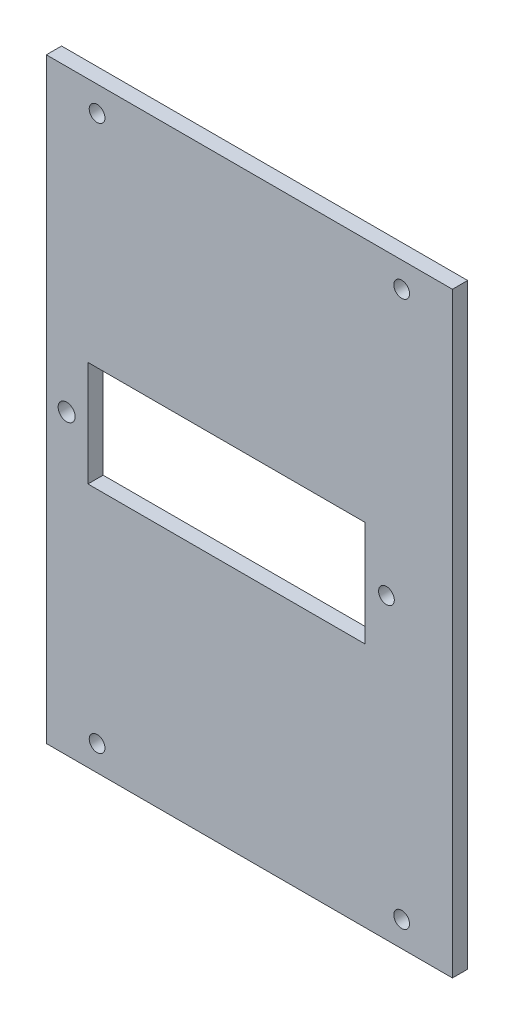
SolidWorks part; units mm, degrees
ref_plane "前视基准面" through (0, 0, 0) normal (0, 0, 1) x (1, 0, 0)
ref_plane "上视基准面" through (0, 0, 0) normal (0, 1, 0) x (1, 0, 0)
ref_plane "右视基准面" through (0, 0, 0) normal (1, 0, 0) x (0, 0, -1)
other "Configuration Table"
sketch "草图1" plane through (0, 0, 0) normal (0, 0, 1) x (1, 0, 0)
  line L0 (40, 117.5) -> (40, 94.3823) construction
  line L1 (0, 0) -> (80, 0)
  line L2 (0, 0) -> (0, 117.5)
  line L3 (0, 117.5) -> (80, 117.5)
  line L4 (80, 0) -> (80, 117.5)
  line L5 (80, 58.75) -> (41.8551, 58.75) construction
  line L7 (22.5, 66.25) -> (57.5, 66.25)
  line L8 (22.5, 66.25) -> (22.5, 51.25)
  line L9 (22.5, 51.25) -> (57.5, 51.25)
  line L10 (57.5, 66.25) -> (57.5, 51.25)
  line L11 (22.5, 66.25) -> (57.5, 51.25) construction
  line L12 (22.5, 51.25) -> (57.5, 66.25) construction
  point P9 (40, 58.75)
  point P10 (40, 58.75)
  dimension "D1" = 117.5
  dimension "D2" = 80
  dimension "D3" = 15
  dimension "D4" = 35
extrude "凸台-拉伸1" add sketch "草图1" along normal blind 3
sketch "草图2" plane through (0, 0, 3) normal (0, 0, 1) x (1, 0, 0)
  line L0 (0, 58.75) -> (80, 58.75) construction
  line L1 (0, 117.5) -> (0, 0) construction
  line L2 (80, 0) -> (80, 117.5) construction
  line L3 (40, 58.75) -> (40, 66.25) construction
  line L4 (57.5, 66.25) -> (22.5, 66.25) construction
  circle A0 centre (40, 76.75) radius 1.55
  circle A1 centre (40, 40.75) radius 1.55
  dimension "D1" = 3.1
  dimension "D2" = 18
extrude "切除-拉伸1" [suppressed] cut sketch "草图2" against normal up to next
sketch "草图3" plane through (0, 0, 3) normal (0, 0, 1) x (1, 0, 0)
  line L0 (40, 117.5) -> (40, 140.159)
  line L1 (80, 117.5) -> (0, 117.5) construction
  line L2 (22.5, 58.75) -> (37.5505, 58.75) construction
  line L3 (22.5, 66.25) -> (22.5, 51.25) construction
  circle A0 centre (10, 112.5) radius 1.55
  circle A1 centre (70, 112.5) radius 1.55
  circle A2 centre (70, 5) radius 1.55
  circle A3 centre (10, 5) radius 1.55
  dimension "D2" = 3.1
  dimension "D1" = 30
  dimension "D3" = 5
extrude "切除-拉伸2" cut sketch "草图3" against normal up to next contours A0 | A1 | A2 | A3
sketch "草图4" plane through (0, 0, 0) normal (0, 0, -1) x (-1, 0, 0)
  line L1 (-57.5, 51.25) -> (-57.5, 66.25) construction
  line L2 (0, 0) -> (-80, 0) construction
  line L3 (-40, 66.25) -> (-40, 51.25) construction
  line L4 (-57.5, 66.25) -> (-22.5, 66.25) construction
  line L5 (-22.5, 51.25) -> (-57.5, 51.25) construction
  line L6 (-57.5, 58.75) -> (-40, 58.75) construction
  circle A0 centre (-67, 58.75) radius 1.55
  circle A2 centre (-13, 58.75) radius 1.55
  dimension "D1" = 3.1
  dimension "D2" = 9.5
  dimension "D3" = 58.75
extrude "切除-拉伸3" cut sketch "草图4" against normal up to next
sketch "草图5" plane through (0, 0, 0) normal (0, 0, -1) x (-1, 0, 0)
  circle A0 centre (-4, 58.5763) radius 1.6734
extrude "切除-拉伸4" cut sketch "草图5" against normal blind 10
sketch "草图6" plane through (0, 0, 3) normal (0, 0, 1) x (1, 0, 0)
  line L0 (22.5, 66.25) -> (57.5, 51.25) construction
  line L2 (17.1936, 69.1216) -> (62.8064, 69.1216)
  line L3 (17.1936, 69.1216) -> (17.1936, 48.3784)
  line L4 (17.1936, 48.3784) -> (62.8064, 48.3784)
  line L5 (62.8064, 69.1216) -> (62.8064, 48.3784)
  line L6 (17.1936, 69.1216) -> (62.8064, 48.3784) construction
  line L7 (17.1936, 48.3784) -> (62.8064, 69.1216) construction
  point P4 (40, 58.75)
extrude "切除-拉伸5" cut sketch "草图6" against normal blind 10
sketch "草图7" plane through (17.1936, 0, 0) normal (1, 0, 0) x (0, 0, -1)
  line L4 (0, 48.3784) -> (0, 69.1216)
  line L5 (0, 69.1216) -> (-3, 69.1216)
  line L6 (-3, 69.1216) -> (-3, 48.3784)
  line L7 (-3, 48.3784) -> (0, 48.3784)
  line L8 (0, 48.3784) -> (0, 69.1216)
  line L9 (0, 69.1216) -> (-3, 69.1216)
  line L10 (-3, 69.1216) -> (-3, 48.3784)
  line L11 (-3, 48.3784) -> (0, 48.3784)
  dimension "D1" = 0
extrude "切除-拉伸6" cut sketch "草图7" against normal blind 9
